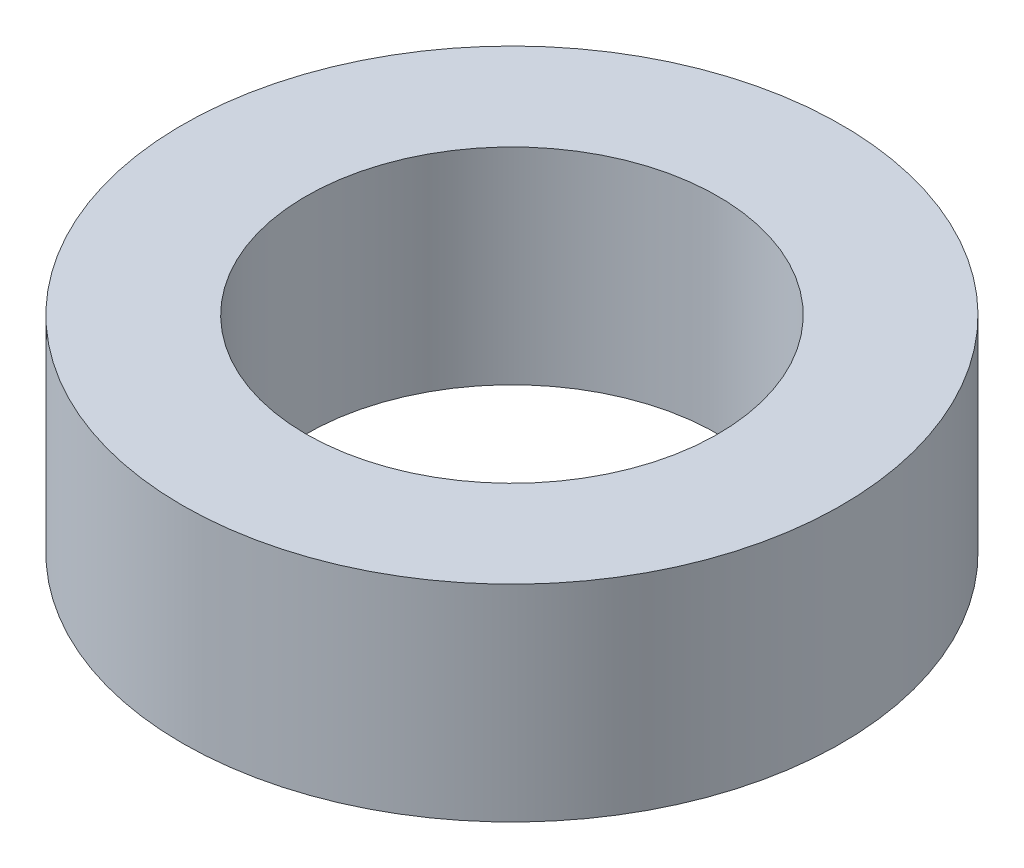
SolidWorks part; units mm, degrees
ref_plane "Front Plane" through (0, 0, 0) normal (0, 0, 1) x (1, 0, 0)
ref_plane "Top Plane" through (0, 0, 0) normal (0, 1, 0) x (1, 0, 0)
ref_plane "Right Plane" through (0, 0, 0) normal (1, 0, 0) x (0, 0, -1)
sketch "Sketch1" plane through (0, 0, 0) normal (0, 1, 0) x (1, 0, 0)
  circle A0 centre (0, 0) radius 2.5
  circle A1 centre (0, 0) radius 4
  dimension "D1" = 5
  dimension "D2" = 8
extrude "Boss-Extrude1" add sketch "Sketch1" along normal mid plane 2.5
